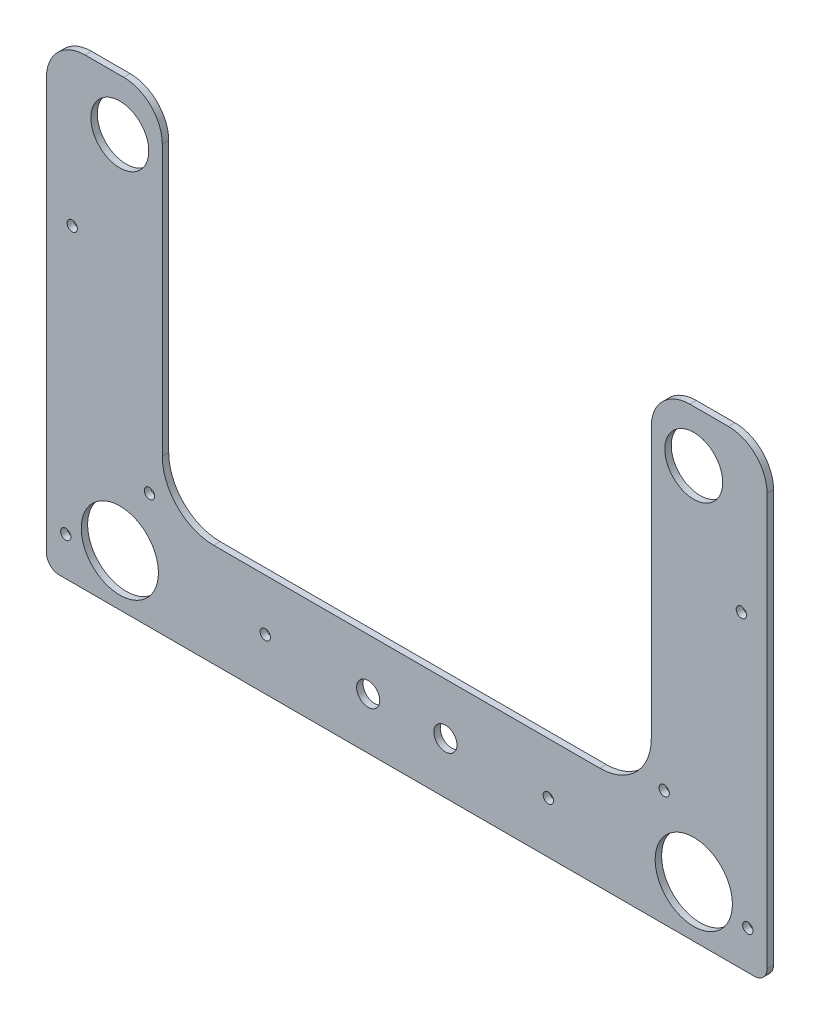
SolidWorks part; units mm, degrees
material "6061 Alloy"
ref_plane "Front Plane" through (0, 0, 0) normal (0, 0, 1) x (1, 0, 0)
ref_plane "Top Plane" through (0, 0, 0) normal (0, 1, 0) x (1, 0, 0)
ref_plane "Right Plane" through (0, 0, 0) normal (1, 0, 0) x (0, 0, -1)
sketch "Sketch1" plane through (0, 0, 0) normal (0, 0, 1) x (1, 0, 0)
  line L5 (120.65, -152.4) -> (120.65, -6.35)
  line L6 (127, 0) -> (171.45, 0) construction
  line L7 (177.8, -6.35) -> (177.8, -222.25)
  line L10 (0, -206.2199) -> (0, -63.6275) construction
  line L11 (-54.9244, 0) -> (300.6756, 0) construction
  line L13 (12.7, -177.8) -> (95.25, -177.8)
  line L14 (12.7, -228.6) -> (171.45, -228.6)
  line L15 (141.605, -25.4) -> (141.605, -84.2822) construction
  line L16 (141.605, -25.4) -> (141.605, -127) construction
  line L19 (-141.605, -19.05) -> (-141.605, -77.9322) construction
  line L20 (141.605, -25.4) -> (141.605, -203.2) construction
  line L22 (-120.65, -152.4) -> (-120.65, -6.35)
  line L23 (-12.7, -177.8) -> (-95.25, -177.8)
  line L24 (-12.7, -228.6) -> (-171.45, -228.6)
  line L25 (-177.8, -6.35) -> (-177.8, -222.25)
  line L26 (-12.7, -177.8) -> (12.7, -177.8)
  line L27 (-12.7, -228.6) -> (12.7, -228.6)
  line L28 (-177.8, -6.35) -> (-177.8, 6.35)
  line L29 (-165.1, 19.05) -> (-133.35, 19.05)
  line L30 (-120.65, 6.35) -> (-120.65, -6.35)
  line L31 (120.65, 6.35) -> (120.65, -6.35)
  line L32 (177.8, -6.35) -> (177.8, 6.35)
  line L33 (165.1, 19.05) -> (133.35, 19.05)
  arc A0 (95.25, -177.8) -> (120.65, -152.4) centre (95.25, -152.4) ccw
  arc A4 (120.65, -6.35) -> (127, 0) centre (127, -6.35) cw construction
  circle A8 centre (141.605, -25.4) radius 14.2875
  circle A9 centre (141.605, -25.4) radius 38.1 construction
  arc A10 (177.8, -6.35) -> (171.45, 0) centre (171.45, -6.35) ccw construction
  arc A11 (171.45, -228.6) -> (177.8, -222.25) centre (171.45, -222.25) ccw
  arc A14 (141.605, -82.55) -> (120.9214, -78.6758) centre (141.605, -25.4) ccw construction
  arc A15 (-141.605, -82.55) -> (-120.9214, -78.6758) centre (-141.605, -25.4) cw construction
  circle A16 centre (-141.605, -25.4) radius 38.1 construction
  circle A17 centre (-141.605, -25.4) radius 14.2875
  arc A19 (-95.25, -177.8) -> (-120.65, -152.4) centre (-95.25, -152.4) cw
  circle A20 centre (141.605, -127) radius 38.1 construction
  circle A21 centre (-141.605, -127) radius 38.1 construction
  arc A23 (-171.45, -228.6) -> (-177.8, -222.25) centre (-171.45, -222.25) cw
  circle A24 centre (-141.605, -203.2) radius 19.05
  circle A37 centre (141.605, -203.2) radius 19.05
  circle A39 centre (-69.85, -203.2) radius 2.54
  circle A40 centre (69.85, -203.2) radius 2.54
  circle A42 centre (-19.05, -203.2) radius 5.715
  arc A44 (-133.35, 19.05) -> (-120.65, 6.35) centre (-133.35, 6.35) cw
  arc A45 (-177.8, 6.35) -> (-165.1, 19.05) centre (-165.1, 6.35) cw
  arc A46 (133.35, 19.05) -> (120.65, 6.35) centre (133.35, 6.35) ccw
  arc A47 (177.8, 6.35) -> (165.1, 19.05) centre (165.1, 6.35) ccw
  circle A50 centre (-149.225, 6.35) radius 2.54
  circle A53 centre (149.225, 6.35) radius 2.54
  circle A54 centre (-168.275, -209.55) radius 2.54
  circle A56 centre (168.275, -209.55) radius 2.54
  circle A58 centre (-165.1, -76.2) radius 2.54
  circle A59 centre (165.1, -76.2) radius 2.54
  circle A60 centre (-127, -171.45) radius 2.54
  circle A61 centre (127, -171.45) radius 2.54
  circle A62 centre (19.05, -203.2) radius 5.715
  point P2 (177.8, -44.45)
  point P18 (177.8, 0)
  point P23 (177.8, -228.6)
  point P24 (177.8, -228.6)
  point P31 (177.8, 0)
  point P48 (-177.8, 0)
  point P49 (-177.8, -228.6)
  point P51 (-177.8, -44.45)
  point P78 (-141.605, -203.2)
  dimension "D6" = 25.4
  dimension "D7" = 6.35
  dimension "D8" = 6.35
  dimension "D9" = 177.8
  dimension "D10" = 28.575
  dimension "D12" = 76.2
  dimension "D13" = 57.15
  dimension "D15" = 38.1
  dimension "D18" = 76.2
  dimension "D21" = 5.08
  dimension "D29" = 9.525
  dimension "D32" = 5.08
  dimension "D35" = 11.43
  dimension "D40" = 12.7
  dimension "D43" = 5.08
  dimension "D45" = 12.7
  dimension "D30" = 5.08
  dimension "D41" = 5.08
  dimension "D22" = 6.35
  dimension "D2" = 120.65
  dimension "D3" = 177.8
  dimension "D4" = 228.6
  dimension "D5" = 177.8
  dimension "D11" = 20.955
  dimension "`" = 25.4
  dimension "D14" = 57.15
  dimension "D16" = 184.15
  dimension "D17" = 101.6
  dimension "D19" = 25.4
  dimension "D20" = 107.95
  dimension "D23" = 57.15
  dimension "D25" = 25.4
  dimension "D26" = 19.05
  dimension "D27" = 25.4
  dimension "D28" = 25.4
  dimension "D31" = 19.05
  dimension "D33" = 12.7
  dimension "D34" = 25.4
  dimension "D39" = 19.05
  dimension "D44" = 28.575
  dimension "D24" = 95.25
extrude "Boss-Extrude3" add sketch "Sketch1" along normal blind 3.175
sketch "Sketch2" plane through (0, 0, 3.175) normal (0, 0, 1) x (1, 0, 0)
  line L0 (177.8, -222.25) -> (177.8, 6.35) construction
  line L1 (-177.8, 19.05) -> (177.8, 19.05)
  line L2 (-177.8, 19.05) -> (-177.8, 0)
  line L3 (-177.8, 0) -> (177.8, 0)
  line L4 (177.8, 19.05) -> (177.8, 0)
  line L5 (-177.8, 6.35) -> (-177.8, -222.25) construction
  line L7 (-133.35, 19.05) -> (-165.1, 19.05) construction
  dimension "D1" = 19.05
extrude "Cut-Extrude1" cut sketch "Sketch2" against normal through all
fillet "Fillet1" radius 19.05 4 edges at (177.8, 0, 1.5875) (120.65, 0, 1.5875) (-120.65, 0, 1.5875) (-177.8, 0, 1.5875)
